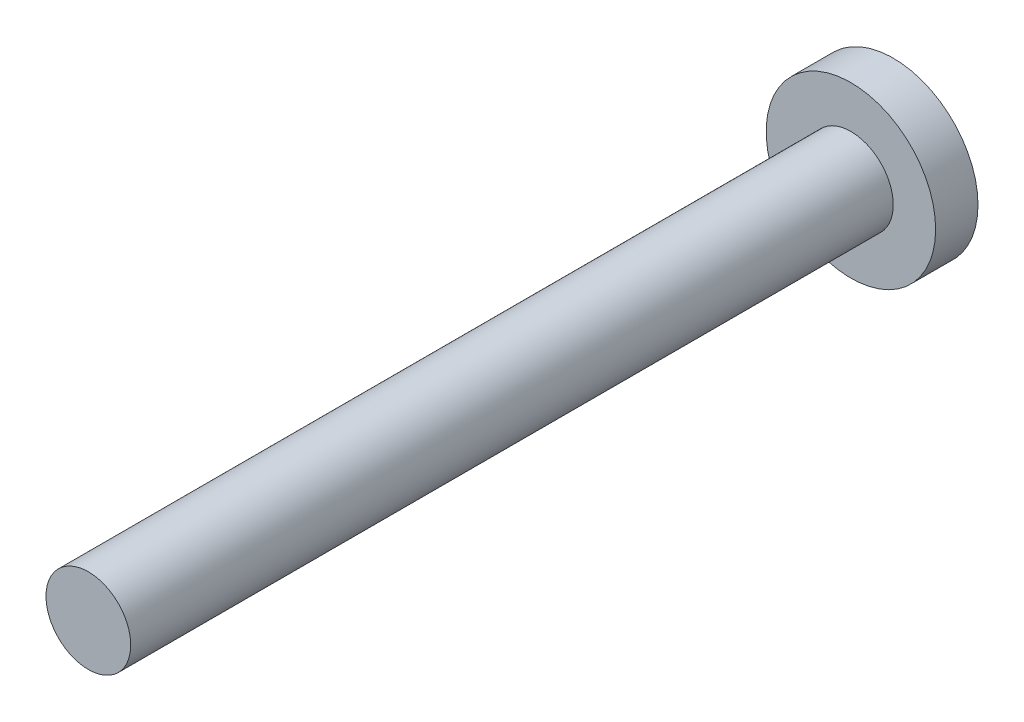
SolidWorks part; units mm, degrees
ref_plane "Piano frontale" through (0, 0, 0) normal (0, 0, 1) x (1, 0, 0)
ref_plane "Piano superiore" through (0, 0, 0) normal (0, 1, 0) x (1, 0, 0)
ref_plane "Piano destro" through (0, 0, 0) normal (1, 0, 0) x (0, 0, -1)
sketch "Schizzo1" plane through (0, 0, 0) normal (0, 0, 1) x (1, 0, 0)
  circle A0 centre (0, 0) radius 10
  dimension "D1" = 20
extrude "Estrusione-Estrusione1" add sketch "Schizzo1" along normal blind 5
sketch "Schizzo2" plane through (0, 0, 5) normal (0, 0, 1) x (1, 0, 0)
  circle A0 centre (0, 0) radius 5
  dimension "D1" = 10
extrude "Estrusione-Estrusione2" add sketch "Schizzo2" along normal blind 90
